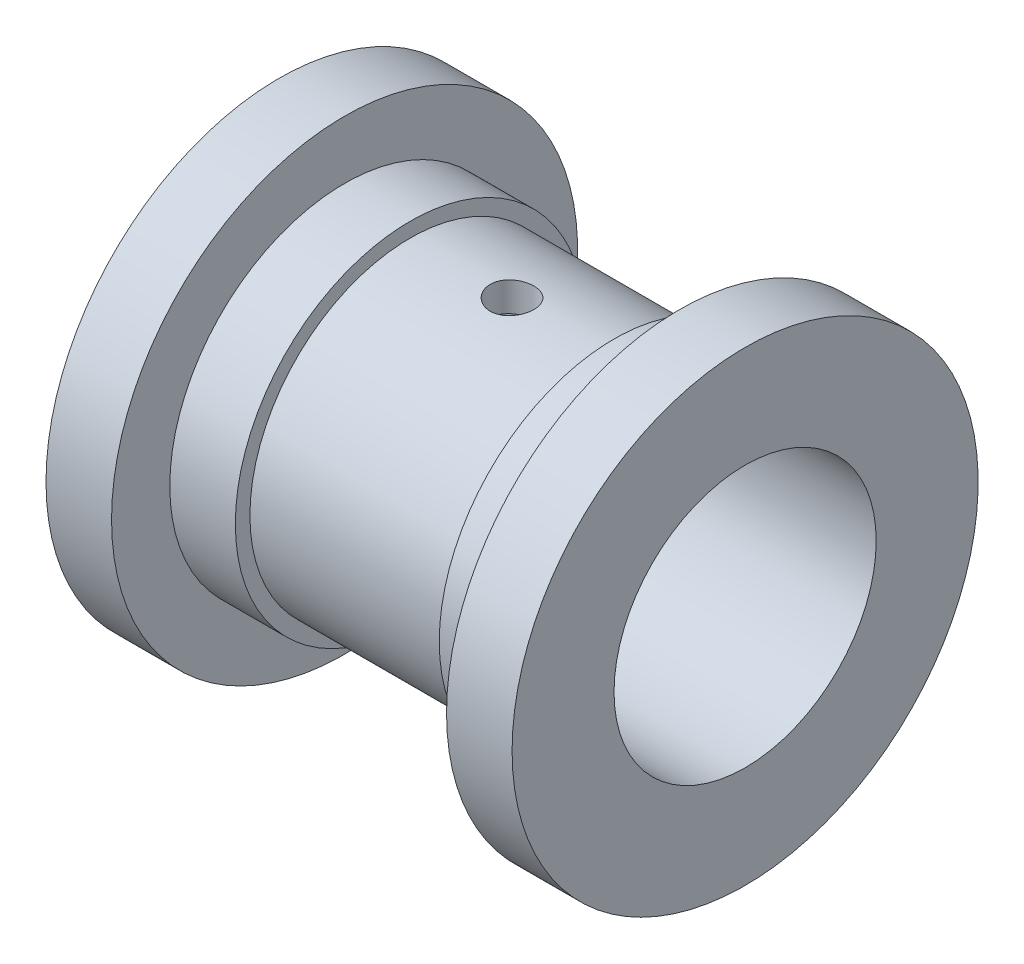
SolidWorks part; units mm, degrees
ref_plane "Front Plane" through (0, 0, 0) normal (0, 0, 1) x (1, 0, 0)
ref_plane "Top Plane" through (0, 0, 0) normal (0, 1, 0) x (1, 0, 0)
ref_plane "Right Plane" through (0, 0, 0) normal (1, 0, 0) x (0, 0, -1)
sketch "Sketch1" plane through (0, 0, 0) normal (0, 0, 1) x (1, 0, 0)
  line L0 (-55.6977, 0) -> (44.7355, 0) construction
  line L1 (-32, 18) -> (-32, 32)
  line L2 (-32, 32) -> (-23, 32)
  line L3 (-23, 32) -> (-23, 24)
  line L4 (-23, 24) -> (-14, 24)
  line L5 (-14, 24) -> (-14, 22)
  line L6 (-14, 22) -> (14, 22)
  line L7 (14, 22) -> (14, 24)
  line L8 (14, 24) -> (23, 24)
  line L9 (23, 24) -> (23, 32)
  line L10 (23, 32) -> (32, 32)
  line L11 (32, 32) -> (32, 18)
  line L12 (32, 18) -> (-32, 18)
  point P11 (-14, 23)
  point P16 (14, 23)
  dimension "D1" = 64
  dimension "D2" = 46
  dimension "D3" = 28
  dimension "D4" = 32
  dimension "D5" = 23
  dimension "D6" = 14
  dimension "D7" = 32
  dimension "D8" = 24
  dimension "D9" = 22
  dimension "D10" = 18
revolve "Revolve1" add sketch "Sketch1" angle 360 about L0
ref_plane "Plane1" through (0, -30, 0) normal (0, 1, 0) x (1, 0, 0)
sketch "Sketch2" plane through (0, -30, 0) normal (0, 1, 0) x (1, 0, 0)
  circle A0 centre (0, 0) radius 4
  circle A1 centre (0, 0) radius 3
  dimension "D1" = 8
  dimension "D2" = 6
extrude "Boss-Extrude1" add sketch "Sketch2" along normal up to next
sketch "Sketch3" plane through (0, -30, 0) normal (0, -1, 0) x (1, 0, 0)
  circle A0 centre (0, 0) radius 3 construction
  circle A1 centre (0, 0) radius 3
extrude "Cut-Extrude1" cut sketch "Sketch3" against normal through all
